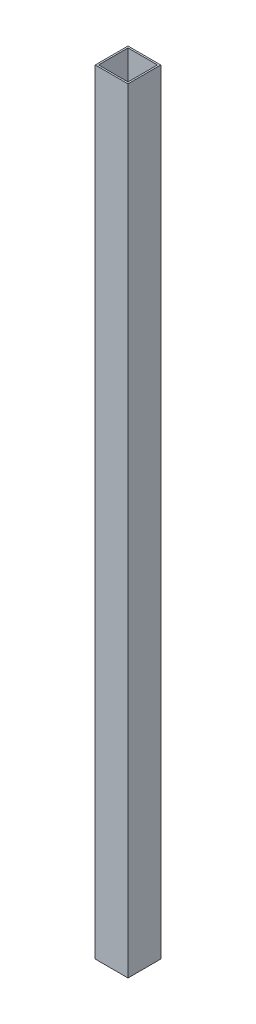
SolidWorks part; units mm, degrees
ref_plane "Front Plane" through (0, 0, 0) normal (0, 0, 1) x (1, 0, 0)
ref_plane "Top Plane" through (0, 0, 0) normal (0, 1, 0) x (1, 0, 0)
ref_plane "Right Plane" through (0, 0, 0) normal (1, 0, 0) x (0, 0, -1)
sketch "Sketch1" plane through (0, 0, 0) normal (0, 1, 0) x (1, 0, 0)
  line L1 (25.4, 25.4) -> (0, 25.4)
  line L2 (25.4, 25.4) -> (25.4, 0)
  line L3 (25.4, 0) -> (0, 0)
  line L4 (0, 25.4) -> (0, 0)
  line L5 (1.27, 1.27) -> (24.13, 1.27)
  line L6 (1.27, 1.27) -> (1.27, 24.13)
  line L7 (1.27, 24.13) -> (24.13, 24.13)
  line L8 (24.13, 1.27) -> (24.13, 24.13)
  line L9 (24.13, 24.13) -> (25.4, 24.13) construction
  line L10 (24.13, 24.13) -> (24.13, 25.4) construction
  line L11 (24.13, 25.4) -> (25.4, 25.4) construction
  line L12 (25.4, 24.13) -> (25.4, 25.4) construction
  line L13 (1.27, 1.27) -> (0, 1.27) construction
  line L14 (1.27, 1.27) -> (1.27, 0) construction
  line L15 (1.27, 0) -> (0, 0) construction
  line L16 (0, 1.27) -> (0, 0) construction
  dimension "D1" = 1.27
  dimension "D2" = 25.4
extrude "Boss-Extrude1" add sketch "Sketch1" along normal blind 600
